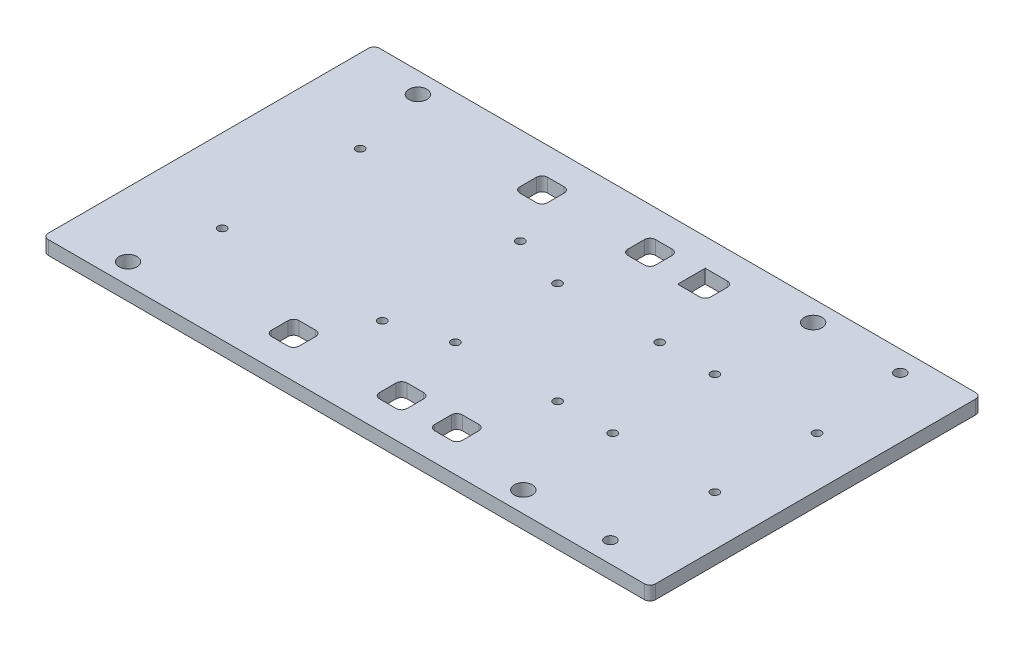
SolidWorks part; units mm, degrees
ref_plane "Front Plane" through (0, 0, 0) normal (0, 0, 1) x (1, 0, 0)
ref_plane "Top Plane" through (0, 0, 0) normal (0, 1, 0) x (1, 0, 0)
ref_plane "Right Plane" through (0, 0, 0) normal (1, 0, 0) x (0, 0, -1)
sketch "Sketch1" plane through (0, 0, 0) normal (0, 1, 0) x (1, 0, 0)
  line L0 (0, 0) -> (-22, 0) construction
  line L1 (-110, 60) -> (110, 60)
  line L2 (-110, 60) -> (-110, -60)
  line L3 (-110, -60) -> (110, -60)
  line L4 (110, 60) -> (110, -60)
  line L5 (-110, 60) -> (110, -60) construction
  line L6 (-110, -60) -> (110, 60) construction
  line L7 (-80, -25) -> (-22, -25) construction
  line L9 (-80, -25) -> (-80, 25) construction
  line L10 (-80, 25) -> (-22, 25) construction
  line L11 (-22, -25) -> (-22, 25) construction
  line L12 (-80, 0) -> (-110, 0) construction
  line L13 (-80, 0) -> (-22, 0) construction
  line L14 (-51, 25) -> (-51, -25) construction
  line L15 (35, 0) -> (110, 0) construction
  line L16 (-2, -18.5) -> (35, -18.5) construction
  line L17 (-2, 0) -> (0, 0)
  line L18 (-2, -18.5) -> (-2, 18.5) construction
  line L19 (-2, 18.5) -> (35, 18.5) construction
  line L20 (35, -18.5) -> (35, 18.5) construction
  line L21 (-2, 0) -> (35, 0) construction
  line L22 (16.5, 18.5) -> (16.5, -18.5) construction
  line L23 (45, 0) -> (45, 32.1156) construction
  circle A0 centre (-22, 25) radius 1.5
  circle A1 centre (-80, 25) radius 1.5
  circle A2 centre (-22, -25) radius 1.5
  circle A3 centre (-80, -25) radius 1.5
  circle A4 centre (-2, 18.5) radius 1.5
  circle A5 centre (35, 18.5) radius 1.5
  circle A6 centre (35, -18.5) radius 1.5
  circle A7 centre (-2, -18.5) radius 1.5
  circle A8 centre (55, -18.5) radius 1.5
  circle A9 centre (92, -18.5) radius 1.5
  circle A10 centre (55, 18.5) radius 1.5
  circle A11 centre (92, 18.5) radius 1.5
  point P0 (0, 0)
  dimension "D5" = 3
  dimension "D9" = 3
  dimension "D1" = 120
  dimension "D2" = 220
  dimension "D3" = 30
  dimension "D4" = 58
  dimension "D6" = 20
  dimension "D7" = 37
  dimension "D8" = 18.5
  dimension "D10" = 10
extrude "Boss-Extrude1" add sketch "Sketch1" along normal blind 5 contours L1 L4 L3 L2 | A1 | A3 | A0 | A2 | A7 | A4 | A5 | A6 | A8 | A10 | A11 | A9
sketch "Sketch2" plane through (0, 0, 0) normal (0, -1, 0) x (1, 0, 0)
  circle A0 centre (56.5935, -52.5) radius 3.25
  circle A1 centre (-86.5935, -52.5) radius 3.25
  circle A2 centre (-86.5935, 52.5) radius 3.25
  circle A3 centre (56.5935, 52.5) radius 3.25
  dimension "D1" = 6.5
  dimension "D2" = 6.5
  dimension "D3" = 6.5
  dimension "D4" = 6.5
extrude "Cut-Extrude1" cut sketch "Sketch2" against normal up to surface (5 mm away) up to face at (55, 5, -17)
sketch "Sketch3" plane through (0, 5, 0) normal (0, 1, 0) x (1, 0, 0)
  line L4 (10, -40) -> (0, -40)
  line L5 (10, -50) -> (10, -40)
  line L6 (0, -50) -> (10, -50)
  line L7 (0, -40) -> (0, -50)
  line L8 (10, -40) -> (0, -40)
  line L9 (10, -50) -> (10, -40)
  line L10 (0, -50) -> (10, -50)
  line L11 (0, -40) -> (0, -50)
  line L12 (20, -50) -> (30, -50)
  line L13 (20, -40) -> (20, -50)
  line L14 (30, -40) -> (20, -40)
  line L15 (30, -50) -> (30, -40)
  line L16 (20, -50) -> (30, -50)
  line L17 (20, -40) -> (20, -50)
  line L18 (30, -40) -> (20, -40)
  line L19 (30, -50) -> (30, -40)
  line L20 (20, 40) -> (30, 40)
  line L21 (20, 50) -> (20, 40)
  line L22 (30, 50) -> (20, 50)
  line L23 (30, 40) -> (30, 50)
  line L24 (20, 40) -> (30, 40)
  line L25 (20, 50) -> (20, 40)
  line L26 (30, 50) -> (20, 50)
  line L27 (30, 40) -> (30, 50)
  line L28 (0, 50) -> (0, 40)
  line L29 (0, 40) -> (10, 40)
  line L30 (10, 40) -> (10, 50)
  line L31 (10, 50) -> (0, 50)
  line L32 (0, 50) -> (0, 40)
  line L33 (0, 40) -> (10, 40)
  line L34 (10, 40) -> (10, 50)
  line L35 (10, 50) -> (0, 50)
  dimension "D1" = 0
  dimension "D2" = 0
  dimension "D3" = 0
  dimension "D4" = 0
extrude "Cut-Extrude2" cut sketch "Sketch3" against normal up to surface (82.7834 mm away)
sketch "Sketch4" plane through (0, 5, 0) normal (0, 1, 0) x (1, 0, 0)
  line L0 (-2.75, 0) -> (2.75, 0) construction
  line L1 (-29.1272, -50) -> (-39.1272, -50)
  line L2 (-29.1272, -50) -> (-29.1272, -40)
  line L3 (-29.1272, -40) -> (-39.1272, -40)
  line L4 (-39.1272, -50) -> (-39.1272, -40)
  line L5 (-39.1272, 50) -> (-39.1272, 40)
  line L6 (-29.1272, 50) -> (-29.1272, 40)
  line L7 (-29.1272, 50) -> (-39.1272, 50)
  line L8 (-29.1272, 40) -> (-39.1272, 40)
  dimension "D1" = 10
  dimension "D2" = 10
extrude "Cut-Extrude3" cut sketch "Sketch4" against normal blind 5
fillet "Fillet1" radius 2 26 edges at (-39.1272, 2.5, -40) (-39.1272, 2.5, -50) (-29.1272, 2.5, -50) (-29.1272, 2.5, -40) (0, 2.5, -40) (0, 2.5, -50) (10, 2.5, -40) (10, 2.5, -50) (30, 2.5, -40) (30, 2.5, -50) (-39.1272, 2.5, 50) (-39.1272, 2.5, 40) (-29.1272, 2.5, 40) (-29.1272, 2.5, 50) (0, 2.5, 50) (0, 2.5, 40) (10, 2.5, 40) (20, 2.5, 40) (30, 2.5, 40) (20, 2.5, 50) (10, 2.5, 50) (30, 2.5, 50) (-110, 2.5, 60) (-110, 2.5, -60) (110, 2.5, -60) (110, 2.5, 60)
sketch "Sketch5" plane through (0, 5, 0) normal (0, 1, 0) x (1, 0, 0)
  circle A0 centre (88.1504, -52.5) radius 2
  circle A1 centre (88.1504, 52.5) radius 2
extrude "Cut-Extrude4" cut sketch "Sketch5" against normal up to surface (5 mm away) up to face at (-34.1272, 0, 45)
